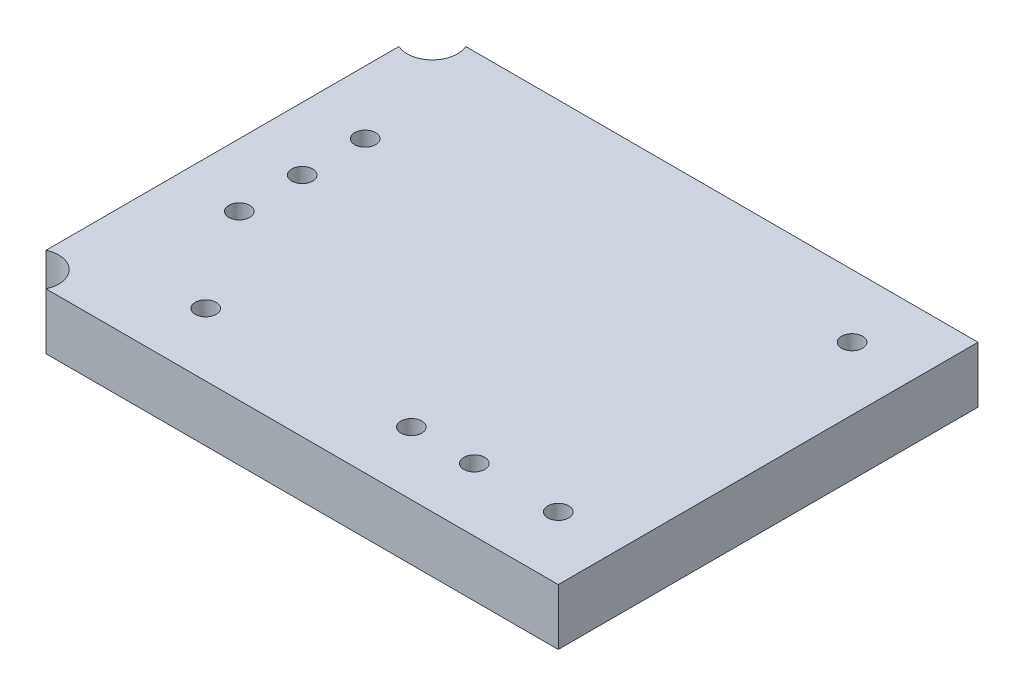
SolidWorks part; units mm, degrees
ref_plane "Front Plane" through (0, 0, 0) normal (0, 0, 1) x (1, 0, 0)
ref_plane "Top Plane" through (0, 0, 0) normal (0, 1, 0) x (1, 0, 0)
ref_plane "Right Plane" through (0, 0, 0) normal (1, 0, 0) x (0, 0, -1)
sketch "Sketch1" plane through (0, 0, 0) normal (0, 1, 0) x (1, 0, 0)
  line L0 (-7.5, 6) -> (7.5, 6) construction
  line L1 (-6.5, 5) -> (6.5, 5)
  line L2 (-6.5, 5) -> (-6.5, -5)
  line L3 (-6.5, -5) -> (6.5, -5)
  line L4 (6.5, 5) -> (6.5, -5)
  line L5 (-6.5, 5) -> (6.5, -5) construction
  line L6 (-6.5, -5) -> (6.5, 5) construction
  line L7 (7.5, 6) -> (7.5, -6) construction
  line L8 (-7.5, -6) -> (7.5, -6) construction
  line L9 (-7.5, 6) -> (-7.5, -6) construction
  circle A0 centre (-6.25, 4.75) radius 1
  circle A1 centre (-6.25, -4.75) radius 1
  circle A2 centre (6.25, -4.75) radius 1
  circle A3 centre (6.25, 4.75) radius 1
  circle A4 centre (-6.25, 4.75) radius 0.6
  circle A5 centre (-6.25, -4.75) radius 0.6
  circle A6 centre (6.25, -4.75) radius 0.6
  circle A7 centre (6.25, 4.75) radius 0.6
  point P0 (0, 0)
  dimension "D4" = 2
  dimension "D9" = 1.2
  dimension "D10" = 1.2
  dimension "D11" = 1.2
  dimension "D12" = 1.2
  dimension "D1" = 10
  dimension "D2" = 13
  dimension "D5" = 1.25
  dimension "D6" = 1.25
  dimension "D7" = 1.25
  dimension "D8" = 1.25
  dimension "D3" = 1
extrude "Boss-Extrude1" add sketch "Sketch1" along normal blind 1.34 contours A3 L1 L2 L3 A2 L4 | L1 A3 L4 | L4 A2 L3 | L4 A6 L3 | L1 A7 L4 | A4 L2 A0 L1 | A5 L3 A1 L2
sketch "Sketch2" plane through (0, 1.34, 0) normal (0, 1, 0) x (1, 0, 0)
  line L0 (-6.5, 4.2046) -> (-6.5, -4.2046) construction
  line L1 (5, -3.5) -> (-5, -3.5) construction
  line L2 (5, -3.5) -> (5, 3.5) construction
  line L3 (5, 3.5) -> (-5, 3.5) construction
  line L4 (-5, -3.5) -> (-5, 3.5) construction
  line L5 (5, -3.5) -> (-5, 3.5) construction
  line L6 (5, 3.5) -> (-5, -3.5) construction
  line L7 (-5.7046, 5) -> (6.5, 5) construction
  circle A0 centre (-5, 1.9) radius 0.25
  circle A1 centre (-5, 0.4) radius 0.25
  circle A2 centre (-5, -1.1) radius 0.25
  circle A3 centre (5, 3.5) radius 0.25
  circle A4 centre (5, -3.5) radius 0.25
  circle A5 centre (3, -3.5) radius 0.25
  circle A6 centre (1.5, -3.5) radius 0.25
  circle A7 centre (-3.4, -3.5) radius 0.25
  point P0 (0, 0)
  dimension "D3" = 0.5
  dimension "D4" = 1.5
  dimension "D1" = 1.5
  dimension "D2" = 1.5
  dimension "D5" = 1.5
  dimension "D6" = 1.5
  dimension "D7" = 4.9
  dimension "D8" = 1.6
  dimension "D9" = 1.6
extrude "Cut-Extrude1" cut sketch "Sketch2" against normal through all
